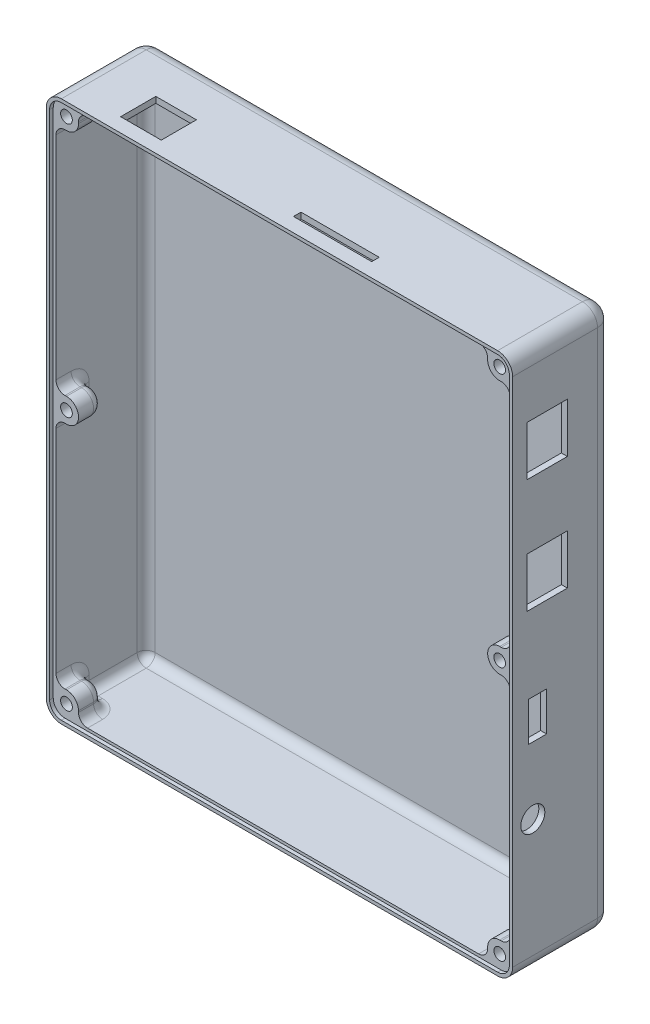
SolidWorks part; units mm, degrees
ref_plane "Front Plane" through (0, 0, 0) normal (0, 0, 1) x (1, 0, 0)
ref_plane "Top Plane" through (0, 0, 0) normal (0, 1, 0) x (1, 0, 0)
ref_plane "Right Plane" through (0, 0, 0) normal (1, 0, 0) x (0, 0, -1)
sketch "Sketch1" plane through (0, 0, 0) normal (0, 0, 1) x (1, 0, 0)
  line L0 (77.5, 90) -> (-77.5, 90) construction
  line L1 (-77.5, -90) -> (77.5, -90)
  line L2 (-77.5, -90) -> (-77.5, 90)
  line L3 (-77.5, 90) -> (77.5, 90)
  line L4 (77.5, -90) -> (77.5, 90)
  line L5 (-77.5, -90) -> (77.5, 90) construction
  line L6 (-77.5, 90) -> (77.5, -90) construction
  line L7 (77.5, -90) -> (77.5, 90) construction
  point P0 (0, 0)
extrude "Boss-Extrude1" add sketch "Sketch1" along normal blind 32
sketch "Sketch9" plane through (0, 0, 0) normal (1, 0, 0) x (0, 0, -1)
  line L0 (38.8695, 68.2558) -> (0, 90.6971) construction
  line L1 (0, 90.6971) -> (0, 0) construction
  dimension "D1" = 60
ref_plane "Plane1" through (0, 0, 0) normal (-1, 0, 0) x (0, 0.5, 0.866)
ref_plane "Plane2" through (0, 68.0228, -39.273) normal (0, 0.866, -0.5) x (0, 0.5, 0.866)
sketch "Sketch10" plane through (0, 68.0228, -39.273) normal (0, 0.866, -0.5) x (0, 0.5, 0.866)
  line L1 (54.0659, -42.3745) -> (5.0696, -42.3745)
  line L2 (54.0659, -42.3745) -> (54.0659, 42.3745)
  line L3 (54.0659, 42.3745) -> (5.0696, 42.3745)
  line L4 (5.0696, -42.3745) -> (5.0696, 42.3745)
  line L5 (54.0659, -42.3745) -> (5.0696, 42.3745) construction
  line L6 (54.0659, 42.3745) -> (5.0696, -42.3745) construction
  point P0 (29.5678, 0)
extrude "Cut-Extrude6" [suppressed] cut sketch "Sketch10" against normal blind 10
fillet "Fillet2" radius 5 8 edges at (0, 90, 0) (-77.5, 0, 0) (0, -90, 0) (77.5, 0, 0) (-77.5, -90, 16) (77.5, -90, 16) (77.5, 90, 16) (-77.5, 90, 16)
shell "Shell1" thickness 2
sketch "Sketch2" plane through (0, 0, 32) normal (0, 0, 1) x (1, 0, 0)
  line L0 (77.5, 0) -> (-77.5, 0) construction
  line L1 (77.5, -85) -> (77.5, 85) construction
  line L2 (-77.5, 85) -> (-77.5, -85) construction
  line L3 (0, 88) -> (0, -90) construction
  line L4 (72.5, 88) -> (-72.5, 88) construction
  line L5 (-72.5, -90) -> (72.5, -90) construction
  line L6 (72, 80.5) -> (77.5, 80.5)
  line L8 (68, 84.5) -> (68, 90)
  line L9 (72.5, 90) -> (-72.5, 90) construction
  line L12 (68, -84.5) -> (68, -90)
  line L14 (72, -80.5) -> (77.5, -80.5)
  line L15 (-72, -80.5) -> (-77.5, -80.5)
  line L17 (-68, -84.5) -> (-68, -90)
  line L20 (-68, 84.5) -> (-68, 90)
  line L22 (-72, 80.5) -> (-77.5, 80.5)
  line L23 (72, 4) -> (77.5, 4)
  line L24 (77.5, 4) -> (77.5, -4)
  line L25 (77.5, -4) -> (72, -4)
  line L26 (-77.5, -4) -> (-72, -4)
  line L27 (-77.5, 4) -> (-77.5, -4)
  line L28 (-72, 4) -> (-77.5, 4)
  line L33 (-77.5, 85) -> (-77.5, -85)
  line L34 (-72.5, -90) -> (72.5, -90)
  line L35 (77.5, -85) -> (77.5, 85)
  line L36 (72.5, 90) -> (-72.5, 90)
  line L37 (-77.5, 85) -> (-77.5, -85)
  line L38 (-72.5, -90) -> (72.5, -90)
  line L39 (77.5, -85) -> (77.5, 85)
  line L40 (72.5, 90) -> (-72.5, 90)
  circle A0 centre (72, 84.5) radius 1.95
  arc A1 (68, 84.5) -> (72, 80.5) centre (72, 84.5) ccw
  circle A2 centre (72, 84.5) radius 2.8 construction
  arc A3 (68, -84.5) -> (72, -80.5) centre (72, -84.5) cw
  circle A4 centre (72, -84.5) radius 1.95
  circle A5 centre (-72, -84.5) radius 1.95
  arc A6 (-68, -84.5) -> (-72, -80.5) centre (-72, -84.5) ccw
  arc A7 (-68, 84.5) -> (-72, 80.5) centre (-72, 84.5) cw
  circle A8 centre (-72, 84.5) radius 1.95
  circle A9 centre (72, 0) radius 1.95
  arc A10 (72, 4) -> (72, -4) centre (72, 0) ccw
  arc A11 (-72, 4) -> (-72, -4) centre (-72, 0) cw
  circle A12 centre (-72, 0) radius 1.95
  arc A17 (-77.5, -85) -> (-72.5, -90) centre (-72.5, -85) ccw
  arc A18 (72.5, -90) -> (77.5, -85) centre (72.5, -85) ccw
  arc A19 (77.5, 85) -> (72.5, 90) centre (72.5, 85) ccw
  arc A20 (-72.5, 90) -> (-77.5, 85) centre (-72.5, 85) ccw
  arc A21 (-77.5, -85) -> (-72.5, -90) centre (-72.5, -85) ccw
  arc A22 (72.5, -90) -> (77.5, -85) centre (72.5, -85) ccw
  arc A23 (77.5, 85) -> (72.5, 90) centre (72.5, 85) ccw
  arc A24 (-72.5, 90) -> (-77.5, 85) centre (-72.5, 85) ccw
  line M5 (75.5, 85) -> (75.5, -85)
  line M6 (72.5, -88) -> (-72.5, -88)
  line M7 (-75.5, -85) -> (-75.5, 85)
  line M8 (-72.5, 88) -> (72.5, 88)
  arc M51 (-75.5, 85) -> (-72.5, 88) centre (-72.5, 85) cw
  arc M52 (72.5, 88) -> (75.5, 85) centre (72.5, 85) cw
  arc M53 (75.5, -85) -> (72.5, -88) centre (72.5, -85) cw
  arc M54 (-72.5, -88) -> (-75.5, -85) centre (-72.5, -85) cw
  dimension "D1" = 3.9
  dimension "D2" = 8
  dimension "D3" = 0
extrude "Boss-Extrude2" add sketch "Sketch2" against normal blind 6 contours A11 L28 L26 A12 M7 | L17 A6 L15 A5 M7 M54 M6 | A3 L12 L14 A4 M6 M53 M5 | L23 A10 L25 A9 M5 | L8 A1 L6 A0 M5 M52 M8 | A7 L20 L22 A8 M8 M51 M7
sketch "Sketch3" plane through (0, 0, 26) normal (0, 0, -1) x (-1, 0, 0)
  line L47 (-72, 4) -> (-75.5, 4)
  line L48 (-68, 84.5) -> (-68, 88)
  line L49 (-68, 88) -> (-72.5, 88)
  line L50 (-75.5, 85) -> (-75.5, 80.5)
  line L51 (-75.5, 80.5) -> (-72, 80.5)
  line L52 (-68, 84.5) -> (-68, 88)
  line L53 (-68, 88) -> (-72.5, 88)
  line L54 (-75.5, 85) -> (-75.5, 80.5)
  line L55 (-75.5, 80.5) -> (-72, 80.5)
  line L56 (-75.5, 4) -> (-75.5, -4)
  line L57 (-75.5, -4) -> (-72, -4)
  line L58 (-72, 4) -> (-75.5, 4)
  line L59 (-75.5, 4) -> (-75.5, -4)
  line L60 (-75.5, -4) -> (-72, -4)
  line L61 (72, -4) -> (75.5, -4)
  line L62 (72, 80.5) -> (75.5, 80.5)
  line L63 (75.5, 80.5) -> (75.5, 85)
  line L64 (72.5, 88) -> (68, 88)
  line L65 (68, 88) -> (68, 84.5)
  line L66 (72, 80.5) -> (75.5, 80.5)
  line L67 (75.5, 80.5) -> (75.5, 85)
  line L68 (72.5, 88) -> (68, 88)
  line L69 (68, 88) -> (68, 84.5)
  line L70 (75.5, -4) -> (75.5, 4)
  line L71 (75.5, 4) -> (72, 4)
  line L72 (72, -4) -> (75.5, -4)
  line L73 (75.5, -4) -> (75.5, 4)
  line L74 (75.5, 4) -> (72, 4)
  line L76 (68, -84.5) -> (68, -88)
  line L77 (68, -88) -> (72.5, -88)
  line L78 (75.5, -85) -> (75.5, -80.5)
  line L79 (75.5, -80.5) -> (72, -80.5)
  line L80 (68, -84.5) -> (68, -88)
  line L81 (68, -88) -> (72.5, -88)
  line L82 (75.5, -85) -> (75.5, -80.5)
  line L83 (75.5, -80.5) -> (72, -80.5)
  line L84 (-72, -80.5) -> (-75.5, -80.5)
  line L85 (-75.5, -80.5) -> (-75.5, -85)
  line L86 (-72.5, -88) -> (-68, -88)
  line L87 (-68, -88) -> (-68, -84.5)
  line L88 (-72, -80.5) -> (-75.5, -80.5)
  line L89 (-75.5, -80.5) -> (-75.5, -85)
  line L90 (-72.5, -88) -> (-68, -88)
  line L91 (-68, -88) -> (-68, -84.5)
  arc A13 (-72, -4) -> (-72, 4) centre (-72, 0) ccw
  arc A14 (-72.5, 88) -> (-75.5, 85) centre (-72.5, 85) ccw
  arc A15 (-72, 80.5) -> (-68, 84.5) centre (-72, 84.5) ccw
  arc A16 (-72.5, 88) -> (-75.5, 85) centre (-72.5, 85) ccw
  arc A17 (-72, 80.5) -> (-68, 84.5) centre (-72, 84.5) ccw
  arc A18 (-72, -4) -> (-72, 4) centre (-72, 0) ccw
  arc A19 (72, 4) -> (72, -4) centre (72, 0) ccw
  arc A20 (68, 84.5) -> (72, 80.5) centre (72, 84.5) ccw
  arc A21 (75.5, 85) -> (72.5, 88) centre (72.5, 85) ccw
  arc A22 (68, 84.5) -> (72, 80.5) centre (72, 84.5) ccw
  arc A23 (75.5, 85) -> (72.5, 88) centre (72.5, 85) ccw
  arc A24 (72, 4) -> (72, -4) centre (72, 0) ccw
  arc A26 (72.5, -88) -> (75.5, -85) centre (72.5, -85) ccw
  arc A27 (72, -80.5) -> (68, -84.5) centre (72, -84.5) ccw
  arc A28 (72.5, -88) -> (75.5, -85) centre (72.5, -85) ccw
  arc A29 (72, -80.5) -> (68, -84.5) centre (72, -84.5) ccw
  arc A30 (-68, -84.5) -> (-72, -80.5) centre (-72, -84.5) ccw
  arc A31 (-75.5, -85) -> (-72.5, -88) centre (-72.5, -85) ccw
  arc A32 (-68, -84.5) -> (-72, -80.5) centre (-72, -84.5) ccw
  arc A33 (-75.5, -85) -> (-72.5, -88) centre (-72.5, -85) ccw
  dimension "D1" = 0
  dimension "D2" = 0
  dimension "D3" = 0
  dimension "D4" = 0
  dimension "D5" = 0
  dimension "D6" = 0
extrude "Boss-Extrude3" add sketch "Sketch3" along normal blind 2
fillet "Fillet1" radius 3 44 edges at (68, 88, 28) (75.5, 80.5, 28) (75.5, -4, 28) (75.5, 4, 28) (68, -88, 28) (75.5, -80.5, 28) (-68, -88, 28) (-75.5, -80.5, 28) (-75.5, 4, 28) (-75.5, -4, 28) (-68, 88, 28) (-75.5, 80.5, 28) (-73.75, -80.5, 24) (-75.5, -82.75, 24) (-74.6213, -87.1213, 24) (-70.25, -88, 24) (-68, -86.25, 24) (-69.1716, -81.6716, 24) (-73.75, 4, 24) (-75.5, 0, 24) (-73.75, -4, 24) (-68, 0, 24) (-68, 86.25, 24) (-70.25, 88, 24) (-74.6213, 87.1213, 24) (-75.5, 82.75, 24) (-73.75, 80.5, 24) (-69.1716, 81.6716, 24) (73.75, 80.5, 24) (75.5, 82.75, 24) (74.6213, 87.1213, 24) (70.25, 88, 24) (68, 86.25, 24) (69.1716, 81.6716, 24) (73.75, -4, 24) (75.5, 0, 24) (73.75, 4, 24) (68, 0, 24) (68, -86.25, 24) (70.25, -88, 24) (74.6213, -87.1213, 24) (75.5, -82.75, 24) (73.75, -80.5, 24) (69.1716, -81.6716, 24)
sketch "Sketch12" plane through (0, 0, 32) normal (0, 0, 1) x (1, 0, 0)
  line L4 (-77.5, 85) -> (-77.5, -85)
  line L5 (-72.5, -90) -> (72.5, -90)
  line L6 (77.5, -85) -> (77.5, 85)
  line L7 (72.5, 90) -> (-72.5, 90)
  line L8 (-77.5, 85) -> (-77.5, -85)
  line L9 (-72.5, -90) -> (72.5, -90)
  line L10 (77.5, -85) -> (77.5, 85)
  line L11 (72.5, 90) -> (-72.5, 90)
  line L16 (-76.4, 85) -> (-76.4, -85)
  line L17 (-72.5, -88.9) -> (72.5, -88.9)
  line L18 (76.4, -85) -> (76.4, 85)
  line L19 (72.5, 88.9) -> (-72.5, 88.9)
  line L20 (-76.4, 85) -> (-76.4, -85)
  line L21 (-72.5, -88.9) -> (72.5, -88.9)
  line L22 (76.4, -85) -> (76.4, 85)
  line L23 (72.5, 88.9) -> (-72.5, 88.9)
  arc A4 (-77.5, -85) -> (-72.5, -90) centre (-72.5, -85) ccw
  arc A5 (72.5, -90) -> (77.5, -85) centre (72.5, -85) ccw
  arc A6 (77.5, 85) -> (72.5, 90) centre (72.5, 85) ccw
  arc A7 (-72.5, 90) -> (-77.5, 85) centre (-72.5, 85) ccw
  arc A8 (-77.5, -85) -> (-72.5, -90) centre (-72.5, -85) ccw
  arc A9 (72.5, -90) -> (77.5, -85) centre (72.5, -85) ccw
  arc A10 (77.5, 85) -> (72.5, 90) centre (72.5, 85) ccw
  arc A11 (-72.5, 90) -> (-77.5, 85) centre (-72.5, 85) ccw
  arc A16 (-76.4, -85) -> (-72.5, -88.9) centre (-72.5, -85) ccw
  arc A17 (72.5, -88.9) -> (76.4, -85) centre (72.5, -85) ccw
  arc A18 (76.4, 85) -> (72.5, 88.9) centre (72.5, 85) ccw
  arc A19 (-72.5, 88.9) -> (-76.4, 85) centre (-72.5, 85) ccw
  arc A20 (-76.4, -85) -> (-72.5, -88.9) centre (-72.5, -85) ccw
  arc A21 (72.5, -88.9) -> (76.4, -85) centre (72.5, -85) ccw
  arc A22 (76.4, 85) -> (72.5, 88.9) centre (72.5, 85) ccw
  arc A23 (-72.5, 88.9) -> (-76.4, 85) centre (-72.5, 85) ccw
  dimension "D1" = 0
  dimension "D2" = 1.1
extrude "Boss-Extrude4" add sketch "Sketch12" along normal blind 1.2
sketch "Sketch4" plane through (0, 90, 0) normal (0, 1, 0) x (1, 0, 0)
  line L1 (-57.5, -28.5) -> (-44, -28.5)
  line L2 (-57.5, -28.5) -> (-57.5, -16.8)
  line L3 (-57.5, -16.8) -> (-44, -16.8)
  line L4 (-44, -28.5) -> (-44, -16.8)
  line L5 (-57.5, -28.5) -> (-44, -16.8) construction
  line L6 (-57.5, -16.8) -> (-44, -28.5) construction
  line L9 (-44.5, -17.3) -> (-44.5, -16.8) construction
  line L10 (-44.5, -17.3) -> (-44, -17.3) construction
  line L11 (-57, -28) -> (-57, -28.5) construction
  line L12 (-57, -28) -> (-57.5, -28) construction
  point P0 (-50.75, -22.65)
  dimension "D1" = 0.5
extrude "Cut-Extrude1" cut sketch "Sketch4" against normal offset from surface (2 mm away) 2 up to face at (0, 90, 19.1)
sketch "Sketch5" plane through (0, 90, 0) normal (0, 1, 0) x (1, 0, 0)
  line L1 (-0.05, -26) -> (25.95, -26)
  line L2 (-0.05, -26) -> (-0.05, -28.5)
  line L3 (-0.05, -28.5) -> (25.95, -28.5)
  line L4 (25.95, -26) -> (25.95, -28.5)
  line L5 (-0.05, -26) -> (25.95, -28.5) construction
  line L6 (-0.05, -28.5) -> (25.95, -26) construction
  line L11 (30.0427, -26.5) -> (38.0256, -26.5) construction
  line L13 (10.73, -26.5) -> (13.73, -26.5) construction
  line L14 (30.4809, -30.5) -> (37.1035, -30.5) construction
  line L15 (28.3, -30.5) -> (-2.4, -30.5) construction
  point P0 (12.95, -27.25)
  point P7 (12.95, -30.5)
  point P15 (0, 0)
  point P18 (0, 0)
  dimension "D1" = 0.5
  dimension "D2" = 26
  dimension "D4" = 2
extrude "Cut-Extrude2" cut sketch "Sketch5" against normal offset from surface (2 mm away) 2 up to face at (-50.75, 90, 22.65)
sketch "Sketch6" plane through (77.5, 0, 0) normal (1, 0, 0) x (0, 0, -1)
  line L5 (-15, 69.45) -> (-28.5, 69.45)
  line L6 (-15, 69.45) -> (-15, 52.95)
  line L11 (-32, 51.4) -> (-32, 43.4) construction
  line L12 (-15, 31.55) -> (-28.5, 31.55)
  line L14 (-15, 31.55) -> (-15, 15.05)
  line L15 (-15, 15.05) -> (-28.5, 15.05)
  line L16 (-28.5, 31.55) -> (-28.5, 15.05)
  line L17 (-13.01, 13) -> (-13.01, 33.6) construction
  line L18 (-15, 52.95) -> (-28.5, 52.95)
  line L19 (-28.5, 69.45) -> (-28.5, 52.95)
  line L20 (-13.01, 50.9) -> (-13.01, 71.5) construction
  point P4 (-15, 61.2)
  point P14 (-13.01, 23.3)
  point P15 (-14.1883, 66.8886)
  point P18 (-13.01, 61.2)
  point P19 (-15, 23.3)
  dimension "D1" = 3.5
  dimension "D2" = 16.5
  dimension "D3" = 13.5
  dimension "D4" = 16.5
  dimension "D5" = 13.5
  dimension "D6" = 3.5
extrude "Cut-Extrude3" cut sketch "Sketch6" against normal offset from surface (2 mm away) 2 up to face at (77.5, 0, 19.1)
sketch "Sketch7" plane through (77.5, 0, 0) normal (1, 0, 0) x (0, 0, -1)
  line L0 (-32, -90) -> (-32, 90) construction
  line L1 (-21.9, -10.5) -> (-28, -10.5)
  line L2 (-21.9, -10.5) -> (-21.9, -23.5)
  line L3 (-21.9, -23.5) -> (-28, -23.5)
  line L4 (-28, -10.5) -> (-28, -23.5)
  line L5 (-21.9, -10.5) -> (-28, -23.5) construction
  line L6 (-21.9, -23.5) -> (-28, -10.5) construction
  line L7 (-26.5, -10.5) -> (-30.5, -10.5) construction
  line L8 (-32, -19.85) -> (-32, -13.85) construction
  point P0 (-24.95, -17)
  dimension "D1" = 10.1
  dimension "D2" = 13
  dimension "D3" = 4
extrude "Cut-Extrude4" cut sketch "Sketch7" against normal offset from surface (2 mm away) 2 up to face at (77.5, 61.2, 21.75)
sketch "Sketch8" plane through (77.5, 0, 0) normal (-1, 0, 0) x (0, 0, 1)
  line L0 (26.5, -51.2) -> (32, -51.2) construction
  line L1 (32, -51.2) -> (32, -40.2) construction
  line L2 (32, -40.2) -> (26.5, -40.2) construction
  arc A0 (26.5, -40.2) -> (26.5, -51.2) centre (26.5, -45.7) ccw construction
  circle A1 centre (26.5, -45.7) radius 4
  dimension "D1" = 5.5
  dimension "D2" = 8
extrude "Cut-Extrude5" cut sketch "Sketch8" along normal up to surface (2 mm away) up to face at (75.5, -17, 24.95)
